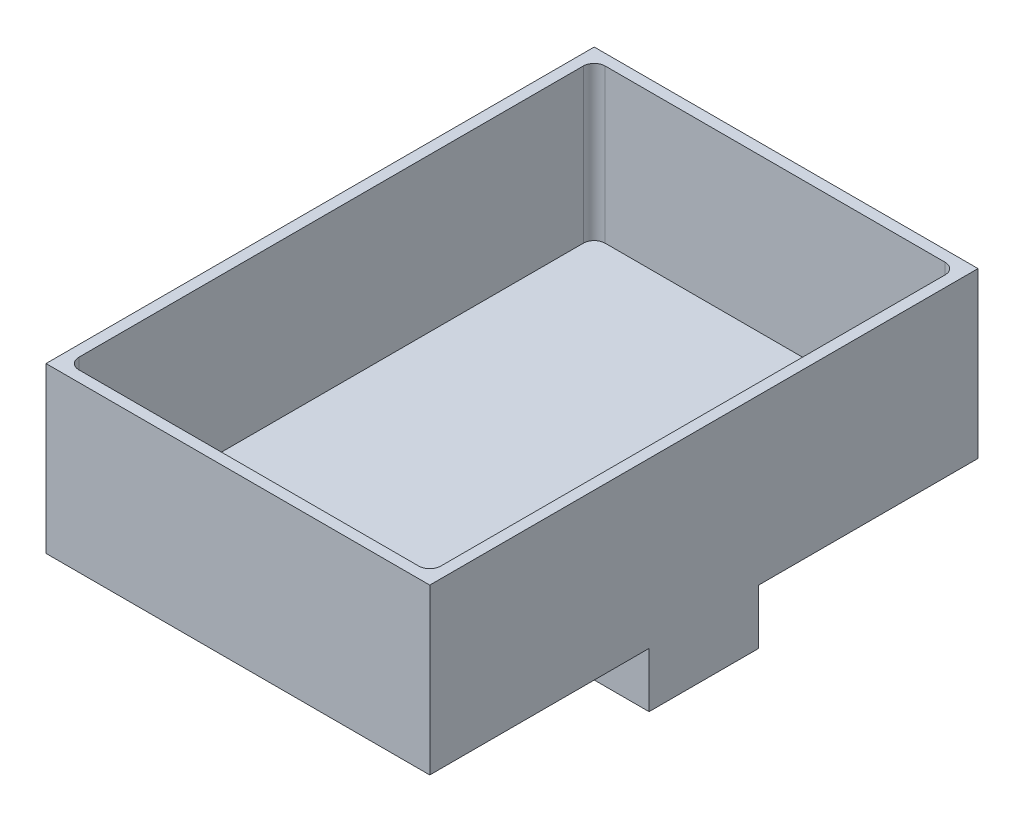
SolidWorks part; units mm, degrees
ref_plane "Front Plane" through (0, 0, 0) normal (0, 0, 1) x (1, 0, 0)
ref_plane "Top Plane" through (0, 0, 0) normal (0, 1, 0) x (1, 0, 0)
ref_plane "Right Plane" through (0, 0, 0) normal (1, 0, 0) x (0, 0, -1)
sketch "Sketch1" plane through (0, 0, 0) normal (1, 0, 0) x (0, 0, -1)
  line L1 (40, 0) -> (60, 0)
  line L2 (0, 10) -> (0, 40)
  line L3 (0, 40) -> (100, 40)
  line L4 (100, 10) -> (100, 40)
  line L7 (0, 10) -> (40, 10)
  line L8 (40, 0) -> (40, 10)
  line L11 (100, 10) -> (60, 10)
  line L12 (60, 0) -> (60, 10)
extrude "Boss-Extrude1" add sketch "Sketch1" along normal blind 70
shell "Shell16" thickness 2
fillet "Fillet1" radius 2 4 edges at (68, 26, -2) (2, 26, -2) (68, 26, -98) (2, 26, -98)
